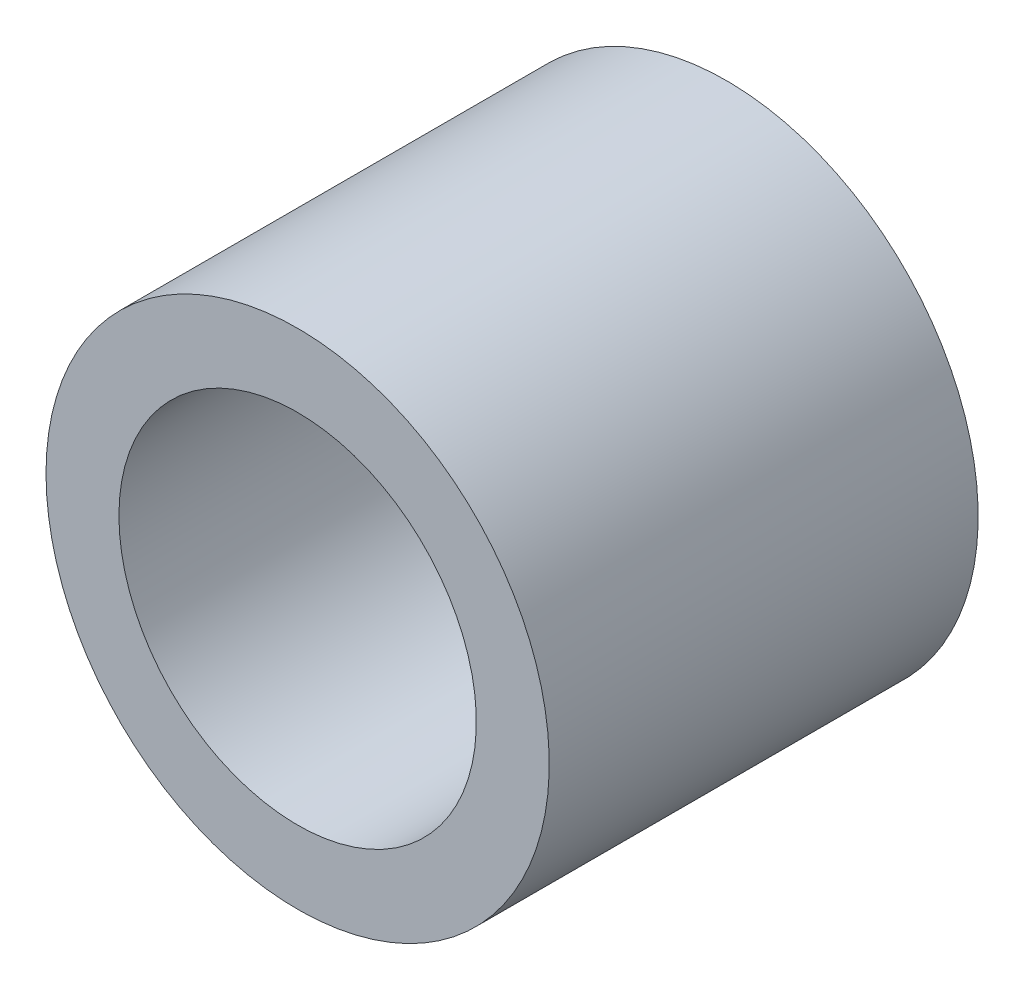
SolidWorks part; units mm, degrees
ref_plane "Front Plane" through (0, 0, 0) normal (0, 0, 1) x (1, 0, 0)
ref_plane "Top Plane" through (0, 0, 0) normal (0, 1, 0) x (1, 0, 0)
ref_plane "Right Plane" through (0, 0, 0) normal (1, 0, 0) x (0, 0, -1)
sketch "Sketch1" plane through (0, 0, 0) normal (0, 0, 1) x (1, 0, 0)
  circle A0 centre (0, 0) radius 5.588
  circle A1 centre (0, 0) radius 3.9688
  dimension "D1" = 11.176
  dimension "ID" = 7.9375
extrude "Extrude1" add sketch "Sketch1" along normal mid plane 9.525
sketch "Sketch2" plane through (0, 0, 0) normal (1, 0, 0) x (0, 0, -1)
  line L0 (-4.7625, -3.9688) -> (4.7625, -3.9688) construction
  line L3 (4.7625, 3.9688) -> (-4.7625, 3.9688) construction
  line L5 (-4.7625, -3.9688) -> (4.7625, -3.9688)
  line L6 (4.7625, 3.9688) -> (-4.7625, 3.9688)
sketch "Sketch4" plane through (0, 0, 4.7625) normal (0, 0, 1) x (1, 0, 0)
  line L0 (0, 0) -> (-2.8063, 2.8063)
  line L1 (0, -15.7442) -> (0, 15.7442) construction
  circle A0 centre (0, 0) radius 3.9688 construction
  dimension "D1" = 45
